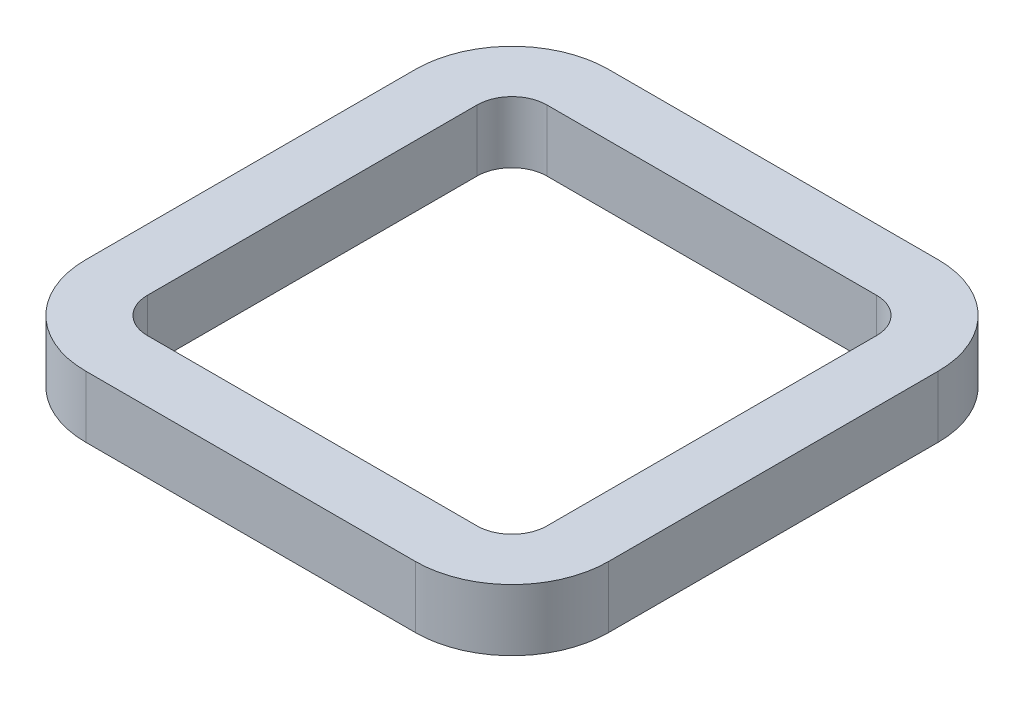
SolidWorks part; units mm, degrees
ref_plane "Front Plane" through (0, 0, 0) normal (0, 0, 1) x (1, 0, 0)
ref_plane "Top Plane" through (0, 0, 0) normal (0, 1, 0) x (1, 0, 0)
ref_plane "Right Plane" through (0, 0, 0) normal (1, 0, 0) x (0, 0, -1)
sketch "Sketch1" plane through (0, 0, 0) normal (0, 1, 0) x (1, 0, 0)
  line L0 (-9.725, 8.025) -> (-9.725, -8.025)
  line L1 (-8.025, 8.025) -> (8.025, 8.025) construction
  line L2 (-8.025, 8.025) -> (-8.025, -8.025) construction
  line L3 (-8.025, -8.025) -> (8.025, -8.025) construction
  line L4 (8.025, 8.025) -> (8.025, -8.025) construction
  line L5 (-8.025, 8.025) -> (8.025, -8.025) construction
  line L6 (-8.025, -8.025) -> (8.025, 8.025) construction
  line L7 (-8.025, -9.725) -> (8.025, -9.725)
  line L8 (9.725, 8.025) -> (9.725, -8.025)
  line L9 (8.025, 9.725) -> (-8.025, 9.725)
  line L10 (-12.725, 8.025) -> (-12.725, -8.025)
  line L11 (-8.025, -12.725) -> (8.025, -12.725)
  line L12 (12.725, 8.025) -> (12.725, -8.025)
  line L13 (8.025, 12.725) -> (-8.025, 12.725)
  circle A0 centre (-8.025, 8.025) radius 1.6 construction
  circle A1 centre (8.025, 8.025) radius 1.6 construction
  circle A2 centre (8.025, -8.025) radius 1.6 construction
  circle A3 centre (-8.025, -8.025) radius 1.6 construction
  arc A4 (-8.025, 9.725) -> (-9.725, 8.025) centre (-8.025, 8.025) ccw
  arc A5 (9.725, 8.025) -> (8.025, 9.725) centre (8.025, 8.025) ccw
  arc A6 (8.025, -9.725) -> (9.725, -8.025) centre (8.025, -8.025) ccw
  arc A7 (-9.725, -8.025) -> (-8.025, -9.725) centre (-8.025, -8.025) ccw
  circle A8 centre (-8.025, 8.025) radius 1.7 construction
  circle A9 centre (8.025, 8.025) radius 1.7 construction
  circle A10 centre (8.025, -8.025) radius 1.7 construction
  circle A11 centre (-8.025, -8.025) radius 1.7 construction
  arc A12 (-12.725, -8.025) -> (-8.025, -12.725) centre (-8.025, -8.025) ccw
  arc A13 (8.025, -12.725) -> (12.725, -8.025) centre (8.025, -8.025) ccw
  arc A14 (12.725, 8.025) -> (8.025, 12.725) centre (8.025, 8.025) ccw
  arc A15 (-8.025, 12.725) -> (-12.725, 8.025) centre (-8.025, 8.025) ccw
  point P0 (0, 0)
  point P26 (8.025, 9.775)
  point P27 (-8.025, 9.775)
  point P28 (8.025, 9.775)
  dimension "D2" = 3.2
  dimension "D1" = 16.05
  dimension "D3" = 0.1
  dimension "D4" = 3
extrude "Boss-Extrude1" add sketch "Sketch1" along normal blind 3
